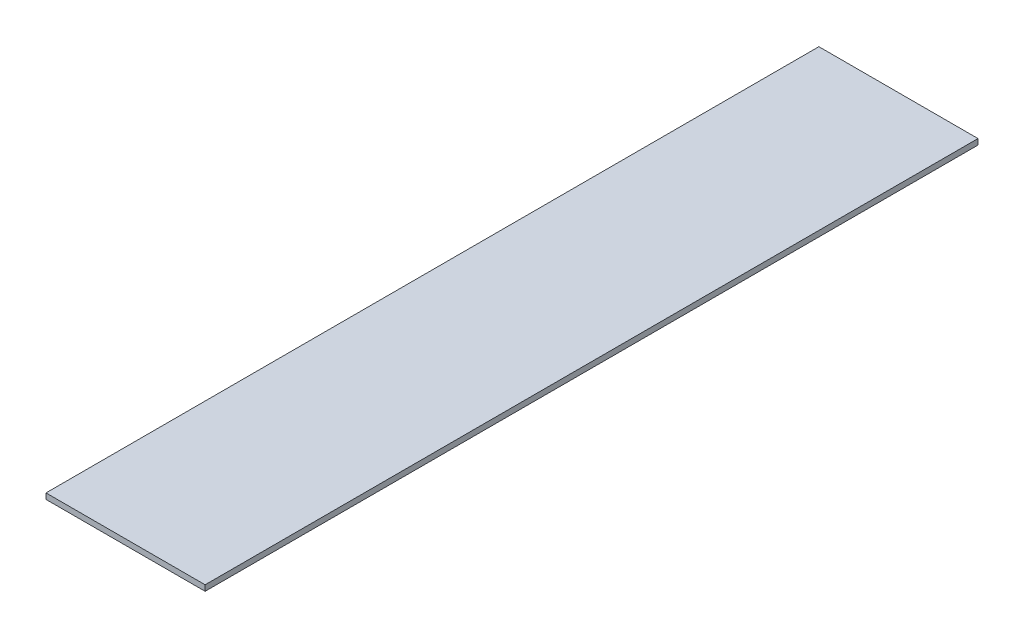
SolidWorks part; units mm, degrees
ref_plane "Front Plane" through (0, 0, 0) normal (0, 0, 1) x (1, 0, 0)
ref_plane "Top Plane" through (0, 0, 0) normal (0, 1, 0) x (1, 0, 0)
ref_plane "Right Plane" through (0, 0, 0) normal (1, 0, 0) x (0, 0, -1)
other "Configuration Table"
sketch "Sketch1" plane through (0, 0, 0) normal (0, 0, 1) x (1, 0, 0)
  line L1 (-70, 255) -> (70, 255)
  line L2 (-70, 255) -> (-70, 260)
  line L3 (-70, 260) -> (70, 260)
  line L4 (70, 255) -> (70, 260)
extrude "KAPYAG_PC_kapak_gecmeli_1" add sketch "Sketch1" against normal blind 680 from offset 20 separate body
